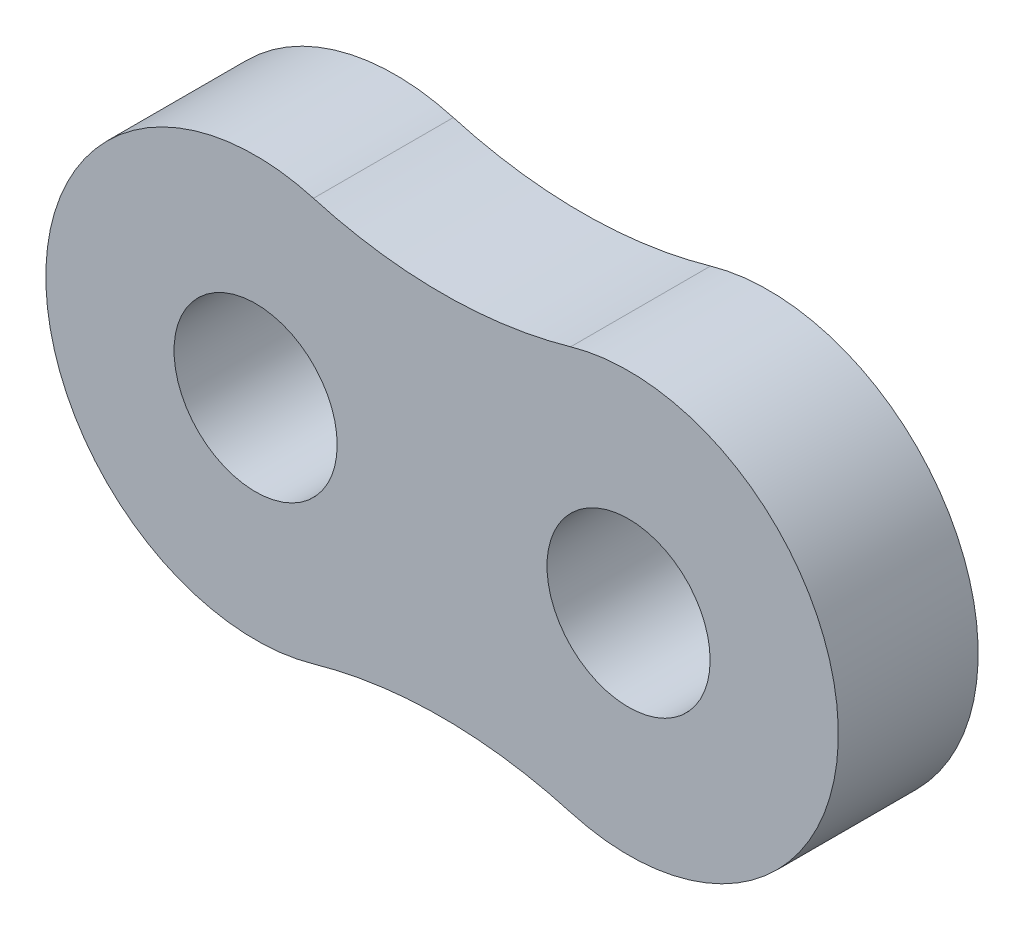
SolidWorks part; units mm, degrees
ref_plane "Спереди" through (0, 0, 0) normal (0, 0, 1) x (1, 0, 0)
ref_plane "Сверху" through (0, 0, 0) normal (0, 1, 0) x (1, 0, 0)
ref_plane "Справа" through (0, 0, 0) normal (1, 0, 0) x (0, 0, -1)
sketch "Эскиз1" plane through (0, 0, 0) normal (0, 0, 1) x (1, 0, 0)
  line L0 (0, 0) -> (78.1966, 0) construction
  circle A0 centre (0, 0) radius 4.5
  circle A1 centre (8, 0) radius 4.5
  circle A2 centre (0, 0) radius 1.75
  circle A3 centre (8, 0) radius 1.75
  dimension "D1" = 9
  dimension "D2" = 9
  dimension "D4" = 3.5
  dimension "D3" = 8
extrude "Бобышка-Вытянуть1" add sketch "Эскиз1" along normal blind 3
fillet "Скругление1" radius 10 2 edges at (4, 2.0616, 1.5) (4, -2.0616, 1.5)
